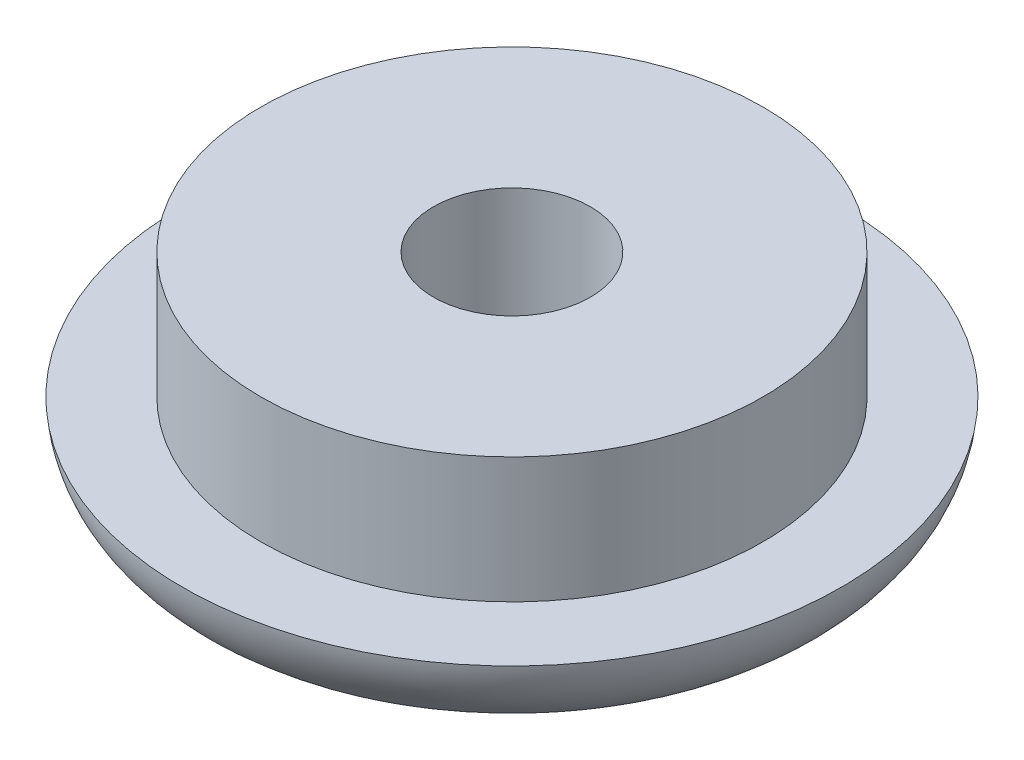
SolidWorks part; units mm, degrees
ref_plane "Front Plane" through (0, 0, 0) normal (0, 0, 1) x (1, 0, 0)
ref_plane "Top Plane" through (0, 0, 0) normal (0, 1, 0) x (1, 0, 0)
ref_plane "Right Plane" through (0, 0, 0) normal (1, 0, 0) x (0, 0, -1)
sketch "Sketch1" plane through (0, 0, 0) normal (0, 0, 1) x (1, 0, 0)
  line L0 (0, 0) -> (0, 19) construction
  line L1 (-2.5, 0) -> (-15, 0)
  line L2 (-2.5, 0) -> (-2.5, 3)
  line L3 (-2.5, 3) -> (-5, 5.5)
  line L4 (-5, 5.5) -> (-5, 13.5)
  line L5 (-5, 13.5) -> (-16, 13.5)
  line L6 (-16, 13.5) -> (-16, 5.5)
  line L7 (-16, 5.5) -> (-21, 5.5)
  line L8 (0, 9.5) -> (-5, 9.5) construction
  arc A0 (-15, 0) -> (-21, 5.5) centre (-15, 6.0227) cw
  dimension "D1" = 19
  dimension "D2" = 8
  dimension "D3" = 42
  dimension "D4" = 5
  dimension "D5" = 5
  dimension "D6" = 10
  dimension "D7" = 30
  dimension "D8" = 45
revolve "Revolve1" add sketch "Sketch1" angle 360 about L0
hole_wizard "M3x0.5 Tapped Hole1" positions "Sketch3" profile "Sketch2" tap size "M3x0.5" standard "ANSI Metric"
sketch "Sketch3" plane through (0, 0, 0) normal (0, -1, 0) x (-1, 0, 0)
  line L0 (-12.5, 0) -> (12.5, 0) construction
  line L3 (0, 9.5) -> (0, -9.5) construction
  point P0 (12.5, 0)
  point P2 (0, 9.5)
  point P4 (-12.5, 0)
  point P6 (0, -9.5)
  dimension "D1" = 25
  dimension "D2" = 19
sketch "Sketch2" plane through (-12.5, 0, 0) normal (1, 0, 0) x (0, 0, -1)
  line L0 (0, 0) -> (0, 5.2511)
  line L1 (0, 5.2511) -> (1.25, 4.5)
  line L2 (1.25, 4.5) -> (1.25, 0)
  line L5 (1.25, 0) -> (0, 0)
  line L10 (0, 5.2511) -> (-1.25, 4.5) construction
  line L11 (0, -6.35) -> (0, 107.95) construction
  dimension "Tap Drill Dia." = 2.5
  dimension "Tap Drill Depth" = 4.5
  dimension "Drill Angle" = 118
